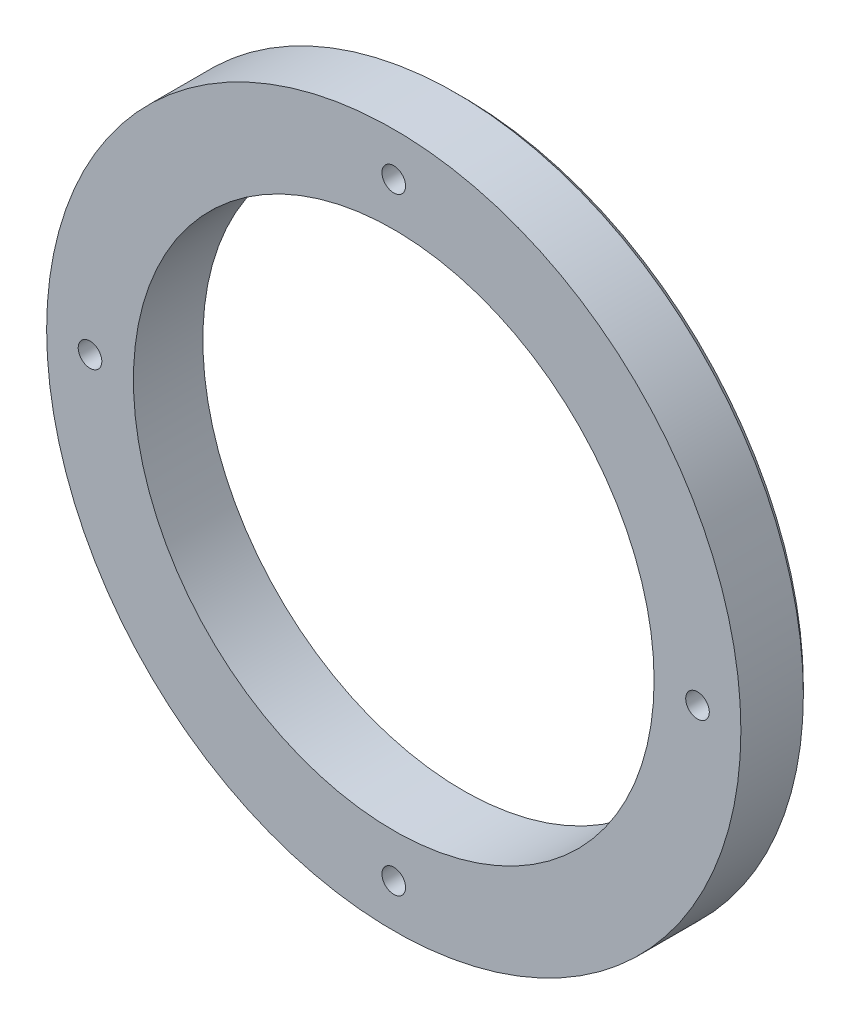
SolidWorks part; units mm, degrees
ref_plane "Płaszczyzna przednia" through (0, 0, 0) normal (0, 0, 1) x (1, 0, 0)
ref_plane "Płaszczyzna górna" through (0, 0, 0) normal (0, 1, 0) x (1, 0, 0)
ref_plane "Płaszczyzna prawa" through (0, 0, 0) normal (1, 0, 0) x (0, 0, -1)
sketch "Szkic1" plane through (0, 0, 0) normal (0, 0, 1) x (1, 0, 0)
  line L0 (0, 110.3916) -> (0, -118.4872) construction
  line L1 (-133.6548, 0) -> (121.6242, 0) construction
  circle A0 centre (0, 0) radius 75
  circle A1 centre (0, 0) radius 100
  circle A2 centre (0, 0) radius 87.5 construction
  circle A3 centre (0, 87.5) radius 3.4
  circle A4 centre (87.5, 0) radius 3.4
  circle A5 centre (0, -87.5) radius 3.4
  circle A6 centre (-87.5, 0) radius 3.4
  point P17 (0, 0)
  dimension "D1" = 150
  dimension "D2" = 200
  dimension "D3" = 12.5
  dimension "D4" = 6.8
extrude "Dodanie-wyciągnięcie1" add sketch "Szkic1" along normal mid plane 20
chamfer "Sfazowanie1" distance 2 angle 45 1 edges at (100, 0, -10)
